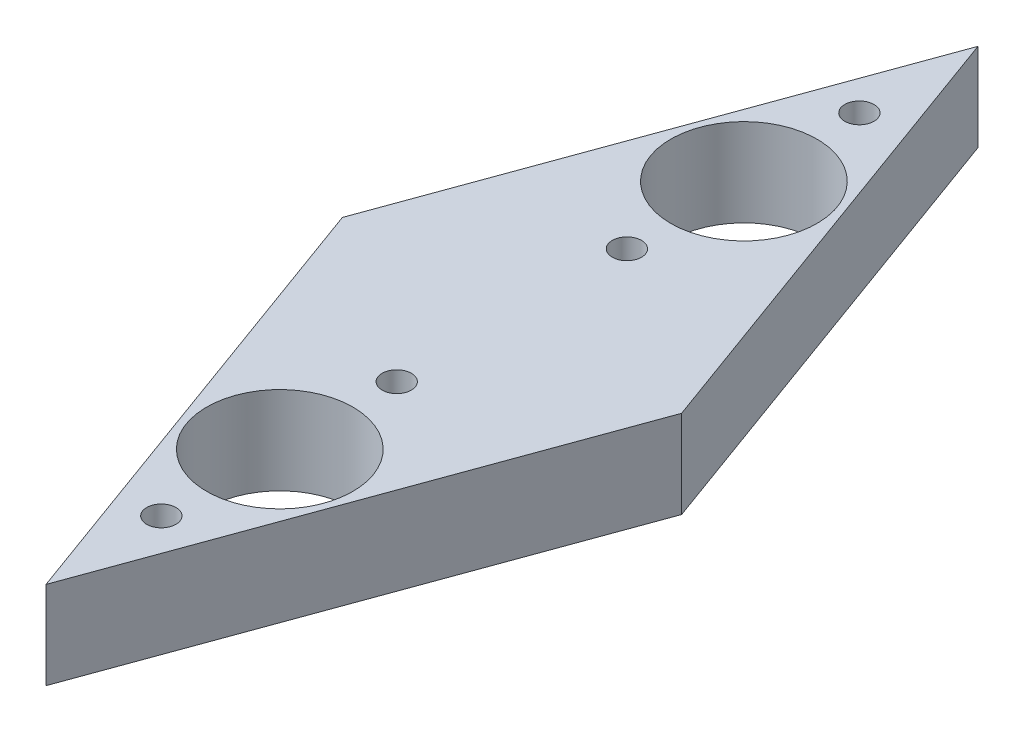
SolidWorks part; units mm, degrees
ref_plane "Front Plane" through (0, 0, 0) normal (0, 0, 1) x (1, 0, 0)
ref_plane "Top Plane" through (0, 0, 0) normal (0, 1, 0) x (1, 0, 0)
ref_plane "Right Plane" through (0, 0, 0) normal (1, 0, 0) x (0, 0, -1)
sketch "Sketch1" plane through (0, 0, 0) normal (0, 1, 0) x (1, 0, 0)
  line L0 (0, 0) -> (29, 79.6768)
  line L1 (29, 79.6768) -> (58, 0)
  line L2 (0, 0) -> (58, 0)
  line L3 (29, -79.6768) -> (58, 0)
  line L4 (0, 0) -> (29, -79.6768)
  dimension "D1" = 58
  dimension "D2" = 70
  dimension "D3" = 70
extrude "Boss-Extrude1" add sketch "Sketch1" along normal blind 15 contours L0 L2 L1 | L2 L4 L3
sketch "Sketch3" plane through (0, 0, 0) normal (0, -1, 0) x (1, 0, 0)
  line L0 (7.1618, 19.6768) -> (50.8382, 19.6768) construction
  line L1 (21.7206, 59.6768) -> (36.2794, 59.6768) construction
  line L2 (0, 0) -> (29, 79.6768) construction
  line L3 (29, 79.6768) -> (58, 0) construction
  line L4 (14.4412, 39.6768) -> (43.5, 39.8384) construction
  line L5 (-7.3131, 0) -> (70.1803, 0) construction
  circle A0 centre (28.7206, 59.6768) radius 2.5
  circle A1 centre (28.9712, 39.6768) radius 12.5
  circle A2 centre (28.9712, 19.6768) radius 2.5
  circle A3 centre (28.7206, -59.6768) radius 2.5
  circle A4 centre (28.9712, -19.6768) radius 2.5
  circle A5 centre (28.9712, -39.6768) radius 12.5
  dimension "D1" = 5
  dimension "D2" = 5
  dimension "D3" = 25
  dimension "D4" = 20
  dimension "D5" = 7
  dimension "D6" = 20
  dimension "D7" = 14.53
  dimension "D8" = 14.5288
  dimension "D9" = 20
  dimension "D10" = 21.8094
extrude "Cut-Extrude1" cut sketch "Sketch3" against normal through all
